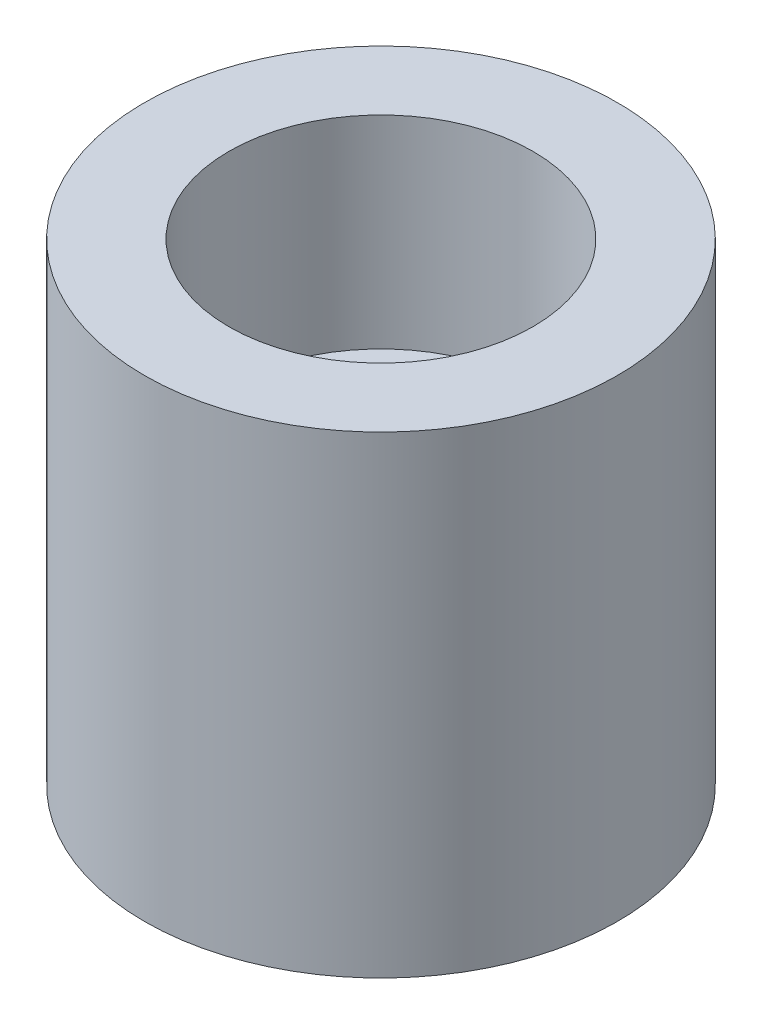
SolidWorks part; units mm, degrees
ref_plane "Alzado" through (0, 0, 0) normal (0, 0, 1) x (1, 0, 0)
ref_plane "Planta" through (0, 0, 0) normal (0, 1, 0) x (1, 0, 0)
ref_plane "Vista lateral" through (0, 0, 0) normal (1, 0, 0) x (0, 0, -1)
sketch "Croquis1" plane through (0, 0, 0) normal (0, 1, 0) x (1, 0, 0)
  circle A0 centre (0, 0) radius 3.5
  dimension "D1" = 7
extrude "Saliente-Extruir1" add sketch "Croquis1" along normal blind 7 contours A0
sketch "Croquis2" plane through (0, 7, 0) normal (0, 1, 0) x (1, 0, 0)
  circle A0 centre (0, 0) radius 2.25
  dimension "D1" = 4.5
extrude "Cortar-Extruir1" cut sketch "Croquis2" against normal blind 3
sketch "Croquis3" plane through (0, 0, 0) normal (0, -1, 0) x (1, 0, 0)
  circle A0 centre (0, 0) radius 2.25
  dimension "D1" = 4.5
extrude "Cortar-Extruir2" cut sketch "Croquis3" against normal blind 1.5
